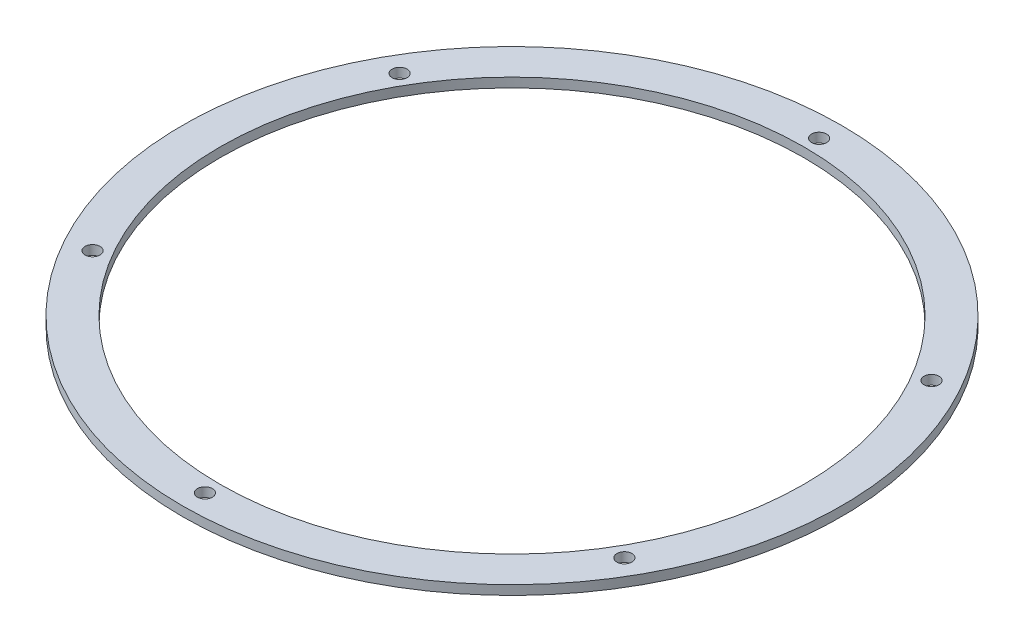
SolidWorks part; units mm, degrees
material "Thornel Mat VMA"
ref_plane "前视基准面" through (0, 0, 0) normal (0, 0, 1) x (1, 0, 0)
ref_plane "上视基准面" through (0, 0, 0) normal (0, 1, 0) x (1, 0, 0)
ref_plane "右视基准面" through (0, 0, 0) normal (1, 0, 0) x (0, 0, -1)
sketch "草图1" plane through (0, 0, 0) normal (0, 1, 0) x (1, 0, 0)
  circle A0 centre (0, 0) radius 88
  circle A1 centre (0, 82) radius 2
  circle A2 centre (0, 0) radius 82 construction
  circle A3 centre (71.0141, 41) radius 2
  circle A4 centre (71.0141, -41) radius 2
  circle A5 centre (0, -82) radius 2
  circle A6 centre (-71.0141, -41) radius 2
  circle A7 centre (-71.0141, 41) radius 2
  circle A14 centre (0, 0) radius 78
  point P30 (0, 0)
  dimension "D1" = 176
  dimension "D2" = 4
  dimension "D3" = 164
  dimension "D5" = 156
  dimension "D4" = 6
extrude "凸台-拉伸1" add sketch "草图1" along normal blind 2.5
